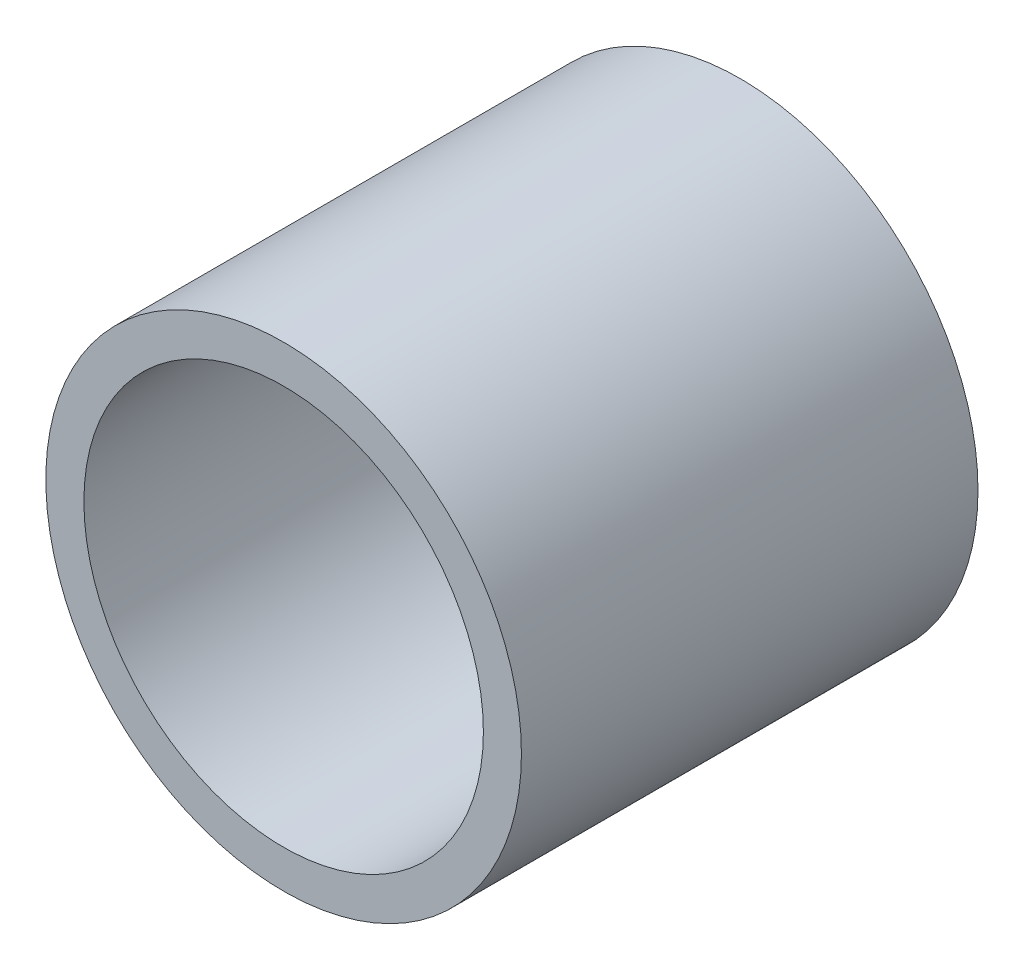
SolidWorks part; units mm, degrees
ref_plane "Front Plane" through (0, 0, 0) normal (0, 0, 1) x (1, 0, 0)
ref_plane "Top Plane" through (0, 0, 0) normal (0, 1, 0) x (1, 0, 0)
ref_plane "Right Plane" through (0, 0, 0) normal (1, 0, 0) x (0, 0, -1)
sketch "Sketch1" plane through (0, 0, 0) normal (0, 0, 1) x (1, 0, 0)
  circle A0 centre (0, 0) radius 1.25
extrude "Boss-Extrude1" add sketch "Sketch1" along normal blind 2.4
sketch "Sketch2" plane through (0, 0, 2.4) normal (0, 0, 1) x (1, 0, 0)
  circle A0 centre (0, 0) radius 1.05
  dimension "D1" = 2.1
extrude "Cut-Extrude1" cut sketch "Sketch2" against normal blind 2
